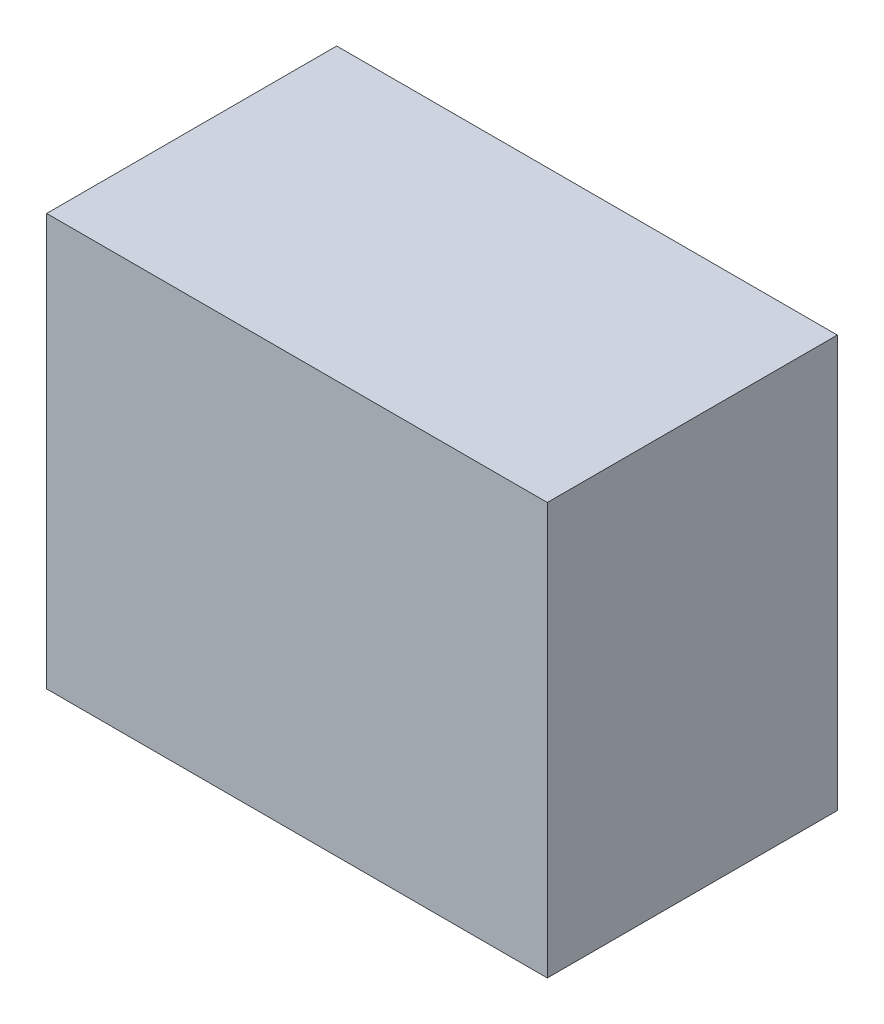
SolidWorks part; units mm, degrees
material "1060 Alloy"
ref_plane "Front" through (0, 0, 0) normal (0, 0, 1) x (1, 0, 0)
ref_plane "Top" through (0, 0, 0) normal (0, 1, 0) x (1, 0, 0)
ref_plane "Right" through (0, 0, 0) normal (1, 0, 0) x (0, 0, -1)
sketch "Sketch3" plane through (0, 0, 0) normal (0, 0, 1) x (1, 0, 0)
  line L0 (-0.127, -6.35) -> (30.1755, -6.35)
  line L1 (0, 0) -> (21.9242, 0)
  line L2 (0, 0) -> (0, -19.8376)
  line L3 (0, -19.8376) -> (21.9242, -19.8376)
  line L4 (21.9242, 0) -> (21.9242, -19.8376)
  line L5 (15.5742, -19.8376) -> (15.5742, 0) construction
  line L6 (15.5742, -6.35) -> (8.0621, -19.3614) construction
  line L15 (12.5496, -11.5887) -> (15.5742, -13.335) construction
  circle A0 centre (15.5742, -6.35) radius 6.0492 construction
  point P14 (0, -6.35)
  point P17 (9.525, -6.35)
  point P20 (7.7871, -19.8376)
  dimension "D2" = 6.35
  dimension "D6" = 3.4925
  dimension "D3" = 60
  dimension "D1" = 9.525
  dimension "D4" = 9.525
  dimension "D5" = 6.35
extrude "Boss-Extrude1" add sketch "Sketch3" along normal mid plane 12.7
sketch "Sketch4" plane through (0, 0, 0) normal (-1, 0, 0) x (0, 0, 1)
  circle A0 centre (0, -6.35) radius 3.175
  dimension "D1" = 6.35
extrude "Cut-Extrude1" cut sketch "Sketch4" against normal blind 9.525
ref_plane "Plane1" through (7.7871, -19.8376, 0) normal (-0.5, -0.866, 0) x (-0.866, 0.5, 0)
ref_plane "Mirror Plane" through (15.5742, 0, 0) normal (-1, 0, 0) x (0, 0, 1)
sketch "Sketch5" plane through (7.7871, -19.8376, 0) normal (-0.5, -0.866, 0) x (-0.866, 0.5, 0)
  circle A0 centre (0, 0) radius 3.175
  dimension "D1" = 6.35
extrude "Cut-Extrude5" cut sketch "Sketch5" against normal blind 9.525 and the other way up to next
sketch "Sketch6" plane through (0, 0, -6.35) normal (0, 0, -1) x (-1, 0, 0)
  circle A0 centre (-15.5742, -6.35) radius 3.175
  dimension "D1" = 6.35
extrude "Cut-Extrude6" cut sketch "Sketch6" against normal blind 9.525
sketch "Sketch7" plane through (21.9242, 0, 0) normal (1, 0, 0) x (0, 0, -1)
  line L0 (-6.35, -19.8376) -> (-6.35, 0) construction
  line L1 (-6.35, -18.034) -> (6.35, -18.034)
  line L2 (-6.35, -18.034) -> (-6.35, -19.8376)
  line L3 (-6.35, -19.8376) -> (6.35, -19.8376)
  line L4 (6.35, -18.034) -> (6.35, -19.8376)
  line L5 (-6.35, 0) -> (6.35, 0) construction
  dimension "D1" = 18.034
extrude "Cut-Extrude7" cut sketch "Sketch7" against normal through all
equation "\"truss_member_od\" = .25in"
equation "\"truss_member_id\"= 0in"
equation "\"truss_member_L1\" = 2.125in"
equation "\"connector_hole_depth\" = .375in"
equation "\"D1@Boss-Extrude1\"=\"truss_member_od\"*2"
equation "\"D6@Sketch3\"=\"truss_member_od\"/2*1.1"
equation "\"D1@Sketch4\"=\"truss_member_od\""
equation "\"D1@Cut-Extrude1\"=\"connector_hole_depth\""
equation "\"D1@Sketch3\"=\"connector_hole_depth\""
equation "\"D4@Sketch3\"=\"connector_hole_depth\""
equation "\"D1@Sketch5\"=\"truss_member_od\""
equation "\"D1@Cut-Extrude5\"=\"connector_hole_depth\""
equation "\"D1@Cut-Extrude6\"=\"connector_hole_depth\""
equation "\"D1@Sketch6\"=\"truss_member_od\""
equation "\"D5@Sketch3\"=\"truss_member_od\""
